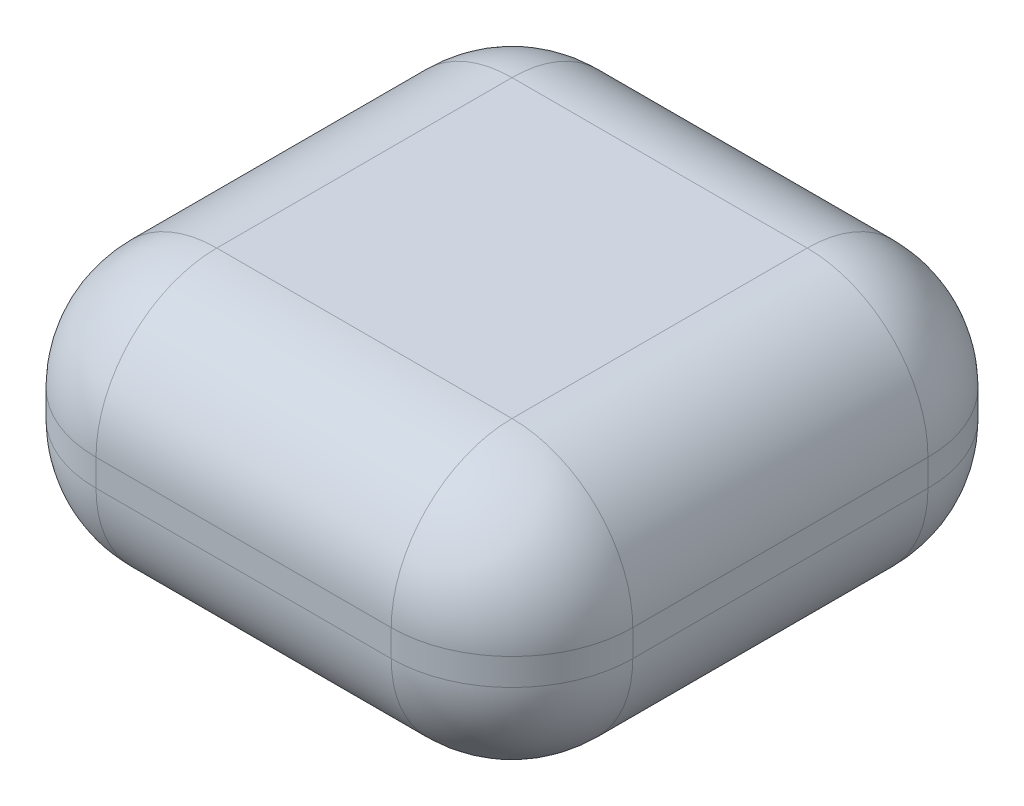
SolidWorks part; units mm, degrees
ref_plane "Front Plane" through (0, 0, 0) normal (0, 0, 1) x (1, 0, 0)
ref_plane "Top Plane" through (0, 0, 0) normal (0, 1, 0) x (1, 0, 0)
ref_plane "Right Plane" through (0, 0, 0) normal (1, 0, 0) x (0, 0, -1)
sketch "Sketch1" plane through (0, 0, 0) normal (0, 0, 1) x (1, 0, 0)
  line L1 (-100, -50) -> (100, -50)
  line L2 (-100, -50) -> (-100, 50)
  line L3 (-100, 50) -> (100, 50)
  line L4 (100, -50) -> (100, 50)
  line L5 (-100, -50) -> (100, 50) construction
  line L6 (-100, 50) -> (100, -50) construction
  point P0 (0, 0)
  dimension "D1" = 100
  dimension "D2" = 200
extrude "Boss-Extrude1" add sketch "Sketch1" along normal mid plane 200
fillet "Fillet1" radius 45 12 edges at (-100, 0, -100) (-100, -50, 0) (0, -50, -100) (100, -50, 0) (100, 0, -100) (0, -50, 100) (-100, 0, 100) (100, 0, 100) (100, 50, 0) (0, 50, 100) (-100, 50, 0) (0, 50, -100)
